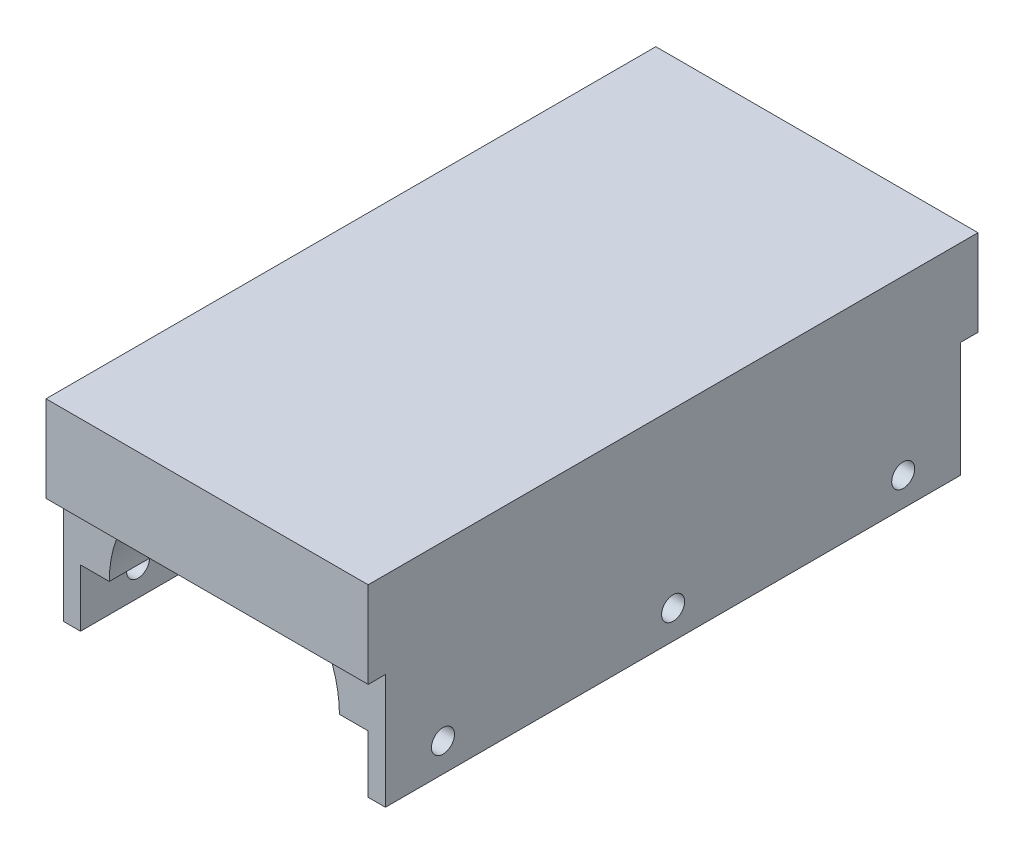
SolidWorks part; units mm, degrees
ref_plane "Front Plane" through (0, 0, 0) normal (0, 0, 1) x (1, 0, 0)
ref_plane "Top Plane" through (0, 0, 0) normal (0, 1, 0) x (1, 0, 0)
ref_plane "Right Plane" through (0, 0, 0) normal (1, 0, 0) x (0, 0, -1)
sketch "Sketch1" plane through (0, 0, 0) normal (0, 0, 1) x (1, 0, 0)
  line L0 (35.812, 0) -> (-35.812, 0) construction
  line L1 (-28, 25) -> (-28, -10)
  line L2 (-28, 25) -> (28, 25)
  line L3 (-28, -10) -> (-25, -10)
  line L4 (-25, -10) -> (-25, 0)
  line L5 (-25, 0) -> (-20, 0)
  line L9 (20, 0) -> (25, 0)
  line L10 (25, 0) -> (25, -10)
  line L11 (25, -10) -> (28, -10)
  line L12 (28, -10) -> (28, 25)
  arc A0 (20, 0) -> (-20, 0) centre (0, 0) ccw
  point P3 (0, 0)
  point P6 (0, 0)
  point P13 (0, 0)
  point P19 (0, 25)
  dimension "D3" = 40
  dimension "D1" = 10
  dimension "D2" = 56
  dimension "D4" = 50
  dimension "D5" = 25
extrude "Boss-Extrude1" add sketch "Sketch1" along normal mid plane 100
sketch "Sketch2" plane through (-25, 0, 0) normal (1, 0, 0) x (0, 0, -1)
  line L4 (50, -10) -> (50, 0)
  line L5 (50, 0) -> (-50, 0)
  line L6 (-50, 0) -> (-50, -10)
  line L7 (-50, -10) -> (50, -10)
  line L8 (50, -10) -> (50, 0) construction
  line L9 (50, 0) -> (-50, 0) construction
  line L10 (-50, 0) -> (-50, -10) construction
  line L11 (-50, -10) -> (50, -10) construction
  circle A0 centre (-40, -5) radius 2
  circle A1 centre (0, -5) radius 2
  circle A2 centre (40, -5) radius 2
  point P10 (0, 0)
  dimension "D2" = 4
  dimension "D4" = 40
  dimension "D6" = 50
  dimension "D3" = 40
  dimension "D5" = 5
  dimension "D1" = 0
extrude "Cut-Extrude1" cut sketch "Sketch2" along normal blind 100 and the other way blind 100
sketch "Sketch3" plane through (0, 0, 50) normal (0, 0, 1) x (1, 0, 0)
  line L0 (28, -10) -> (28, 25) construction
  line L1 (-28, 25) -> (28, 25)
  line L2 (-28, 25) -> (-28, 10)
  line L3 (-28, 10) -> (28, 10)
  line L4 (28, 25) -> (28, 10)
  dimension "D1" = 15
extrude "Boss-Extrude2" add sketch "Sketch3" along normal blind 3
mirror "Mirror1" about plane through (0, 0, 0) normal (0, 0, 1) of "Boss-Extrude2"
